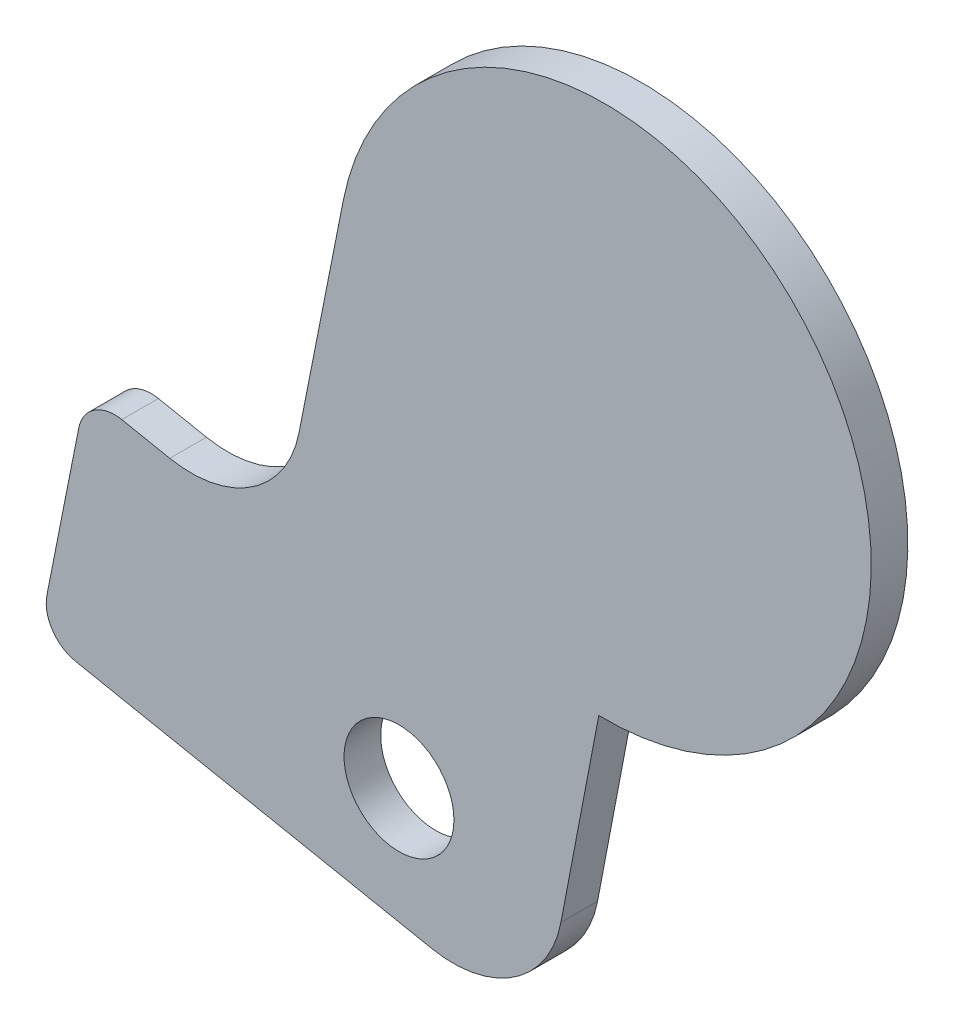
SolidWorks part; units mm, degrees
ref_plane "Front Plane" through (0, 0, 0) normal (0, 0, 1) x (1, 0, 0)
ref_plane "Top Plane" through (0, 0, 0) normal (0, 1, 0) x (1, 0, 0)
ref_plane "Right Plane" through (0, 0, 0) normal (1, 0, 0) x (0, 0, -1)
sketch "Sketch1" plane through (0, 0, 0) normal (0, 0, 1) x (1, 0, 0)
  line L0 (-12.0248, -12.0267) -> (-5.8594, 0.8415) construction
  line L1 (-13.5464, 1.1127) -> (-14.7575, -4.9953)
  line L4 (-18.2837, -7.3545) -> (-19.5941, -7.0946)
  line L5 (-20.7695, -7.881) -> (-21.6394, -12.2677)
  line L6 (-20.853, -13.4431) -> (-11.1335, -15.3704)
  line L7 (-6.5696, -7.5787) -> (-7.6032, -12.9905)
  arc A0 (-6.5696, -7.5787) -> (-13.5464, 1.1127) centre (-6.4077, -0.3028) ccw
  circle A1 centre (-12.0248, -12.0267) radius 1.5
  arc A2 (-14.7575, -4.9953) -> (-18.2837, -7.3545) centre (-17.7002, -4.4118) cw
  arc A3 (-11.1335, -15.3704) -> (-7.6032, -12.9905) centre (-10.55, -12.4277) ccw
  arc A4 (-21.6394, -12.2677) -> (-20.853, -13.4431) centre (-20.6585, -12.4622) ccw
  arc A5 (-19.5941, -7.0946) -> (-20.7695, -7.881) centre (-19.7886, -8.0755) ccw
  point P6 (-9.3193, -13.3229)
  point P7 (-3.1539, -0.4547)
  point P8 (-14.7303, -10.7304)
  point P9 (-8.5649, 2.1378)
  point P20 (-15.341, -7.938)
  point P25 (-21.8339, -13.2486)
  dimension "D1" = 3
  dimension "D2" = 1
extrude "Boss-Extrude1" add sketch "Sketch1" along normal blind 1
